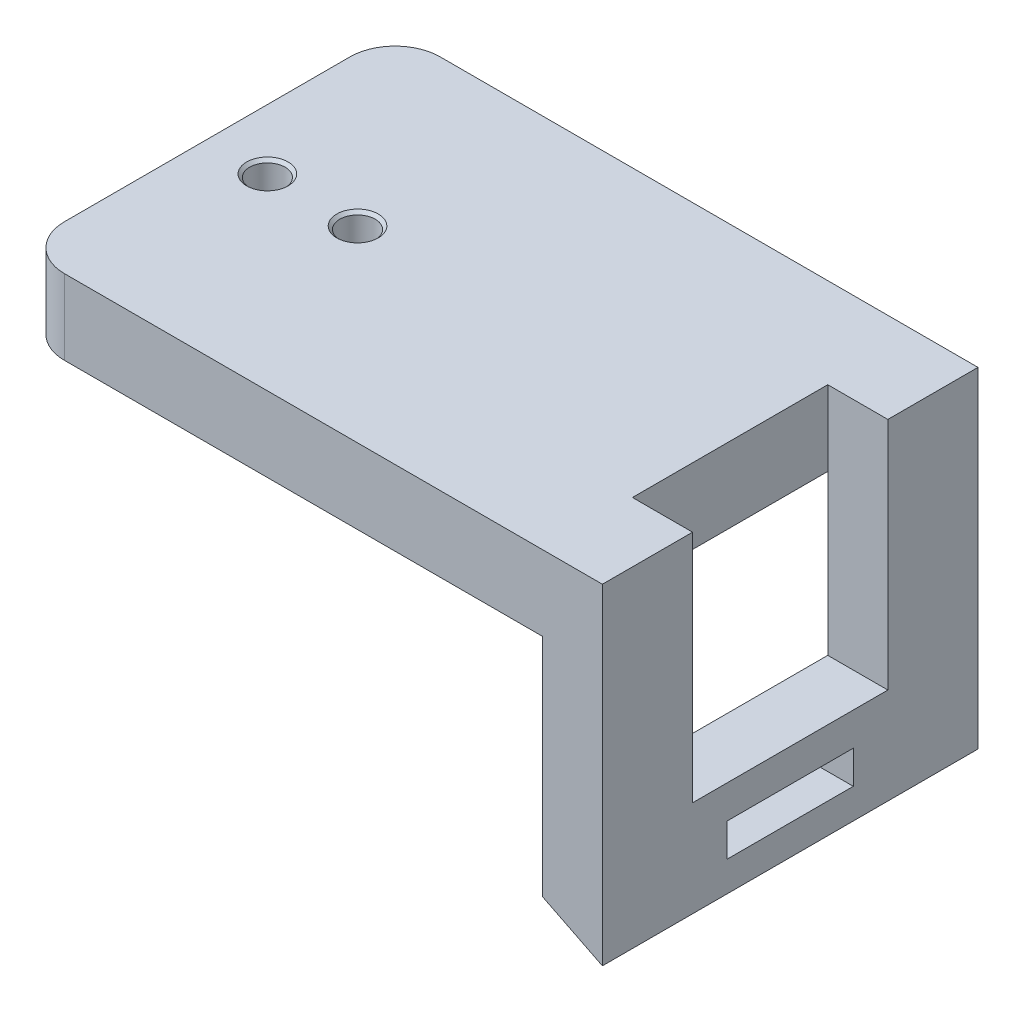
SolidWorks part; units mm, degrees
ref_plane "Front Plane" through (0, 0, 0) normal (0, 0, 1) x (1, 0, 0)
ref_plane "Top Plane" through (0, 0, 0) normal (0, 1, 0) x (1, 0, 0)
ref_plane "Right Plane" through (0, 0, 0) normal (1, 0, 0) x (0, 0, -1)
sketch "Sketch1" plane through (0, 0, 0) normal (0, 1, 0) x (1, 0, 0)
  line L1 (0, 0) -> (44.196, 0)
  line L2 (0, 0) -> (0, 31.75)
  line L3 (0, 31.75) -> (44.196, 31.75)
  line L4 (44.196, 0) -> (44.196, 31.75)
  dimension "D1" = 44.196
  dimension "D2" = 31.75
extrude "Boss-Extrude1" add sketch "Sketch1" along normal blind 6.35
hole_wizard "Ø3.0mm Dowel Hole1" positions "Sketch5" profile "Sketch4" hole size "Ø3.0" standard "ISO" end condition through all
sketch "Sketch5" plane through (0, 6.35, 0) normal (0, 1, 0) x (1, 0, 0)
  line L0 (0, 0) -> (44.196, 0) construction
  line L1 (0, 31.75) -> (0, 0) construction
  point P0 (5.08, 15.875)
  point P2 (12.7, 15.875)
  dimension "D1" = 15.875
  dimension "D2" = 5.08
  dimension "D3" = 7.62
sketch "Sketch4" plane through (5.08, 6.35, -15.875) normal (1, 0, 0) x (0, 0, 1)
  line L0 (0, 0) -> (0, 6.35)
  line L1 (0, 6.35) -> (1.5, 6.35)
  line L2 (1.5, 6.35) -> (1.5, 0)
  line L5 (1.5, 0) -> (0, 0)
  line L11 (0, -6.35) -> (0, 107.95) construction
  dimension "Thru Hole Dia." = 3
  dimension "Thru Hole Depth" = 6.35
chamfer "Chamfer1" distance 0.254 angle 45 4 edges at (12.7, 6.35, -14.375) (5.08, 6.35, -14.375) (5.08, 0, -14.375) (12.7, 0, -14.375)
fillet "Fillet2" radius 3.81 2 edges at (0, 3.175, 0) (0, 3.175, -31.75)
sketch "Sketch6" plane through (44.196, 0, 0) normal (1, 0, 0) x (0, 0, -1)
  line L0 (0, 6.35) -> (0, -19.05)
  line L1 (31.75, 6.35) -> (31.75, -19.05)
  line L2 (31.75, -19.05) -> (0, -19.05)
  line L3 (0, 6.35) -> (7.62, 6.35)
  line L4 (0, 6.35) -> (31.75, 6.35) construction
  line L5 (7.62, 6.35) -> (7.62, -11.43)
  line L6 (7.62, -11.43) -> (24.13, -11.43)
  line L7 (24.13, -11.43) -> (24.13, 6.35)
  line L8 (24.13, 6.35) -> (31.75, 6.35)
  dimension "D1" = 7.62
  dimension "D2" = 7.62
  dimension "D3" = 25.4
  dimension "D4" = 7.62
extrude "Boss-Extrude4" add sketch "Sketch6" along normal blind 5.08
sketch "Sketch7" plane through (44.196, 0, 0) normal (-1, 0, 0) x (0, 0, 1)
  line L0 (0, -19.05) -> (-31.75, -19.05) construction
  line L1 (-21.209, -19.05) -> (-10.541, -19.05)
  line L2 (-21.209, -19.05) -> (-21.209, -16.256)
  line L3 (-21.209, -16.256) -> (-10.541, -16.256)
  line L4 (-10.541, -19.05) -> (-10.541, -16.256)
  line L5 (-24.13, -11.43) -> (-7.62, -11.43) construction
  point P6 (-15.875, -11.43)
  dimension "D1" = 5.334
  dimension "D2" = 10.668
  dimension "D3" = 2.794
extrude "Cut-Extrude1" cut sketch "Sketch7" against normal through all
sketch "Sketch8" plane through (0, -19.05, 0) normal (0, -1, 0) x (1, 0, 0)
  line L1 (44.196, -31.75) -> (49.276, -31.75)
  line L2 (44.196, -31.75) -> (44.196, 0)
  line L3 (44.196, 0) -> (49.276, 0)
  line L4 (49.276, -31.75) -> (49.276, 0)
extrude "Boss-Extrude5" add sketch "Sketch8" along normal blind 2.54
sketch "Sketch9" plane through (0, 0, -31.75) normal (0, 0, -1) x (-1, 0, 0)
  line L0 (-49.276, -21.59) -> (-44.196, -19.05)
  line L1 (-44.196, -21.59) -> (-44.196, 0) construction
  line L2 (-44.196, -19.05) -> (-44.196, -21.59)
  line L3 (-44.196, -21.59) -> (-49.276, -21.59)
  dimension "D1" = 2.54
extrude "Cut-Extrude2" cut sketch "Sketch9" against normal through all
sketch "Sketch10" plane through (0, -11.43, 0) normal (0, 1, 0) x (1, 0, 0)
  line L1 (49.276, 7.62) -> (44.196, 7.62)
  line L2 (49.276, 7.62) -> (49.276, 24.13)
  line L3 (49.276, 24.13) -> (44.196, 24.13)
  line L4 (44.196, 7.62) -> (44.196, 24.13)
extrude "Cut-Extrude3" cut sketch "Sketch10" against normal blind 2.032
